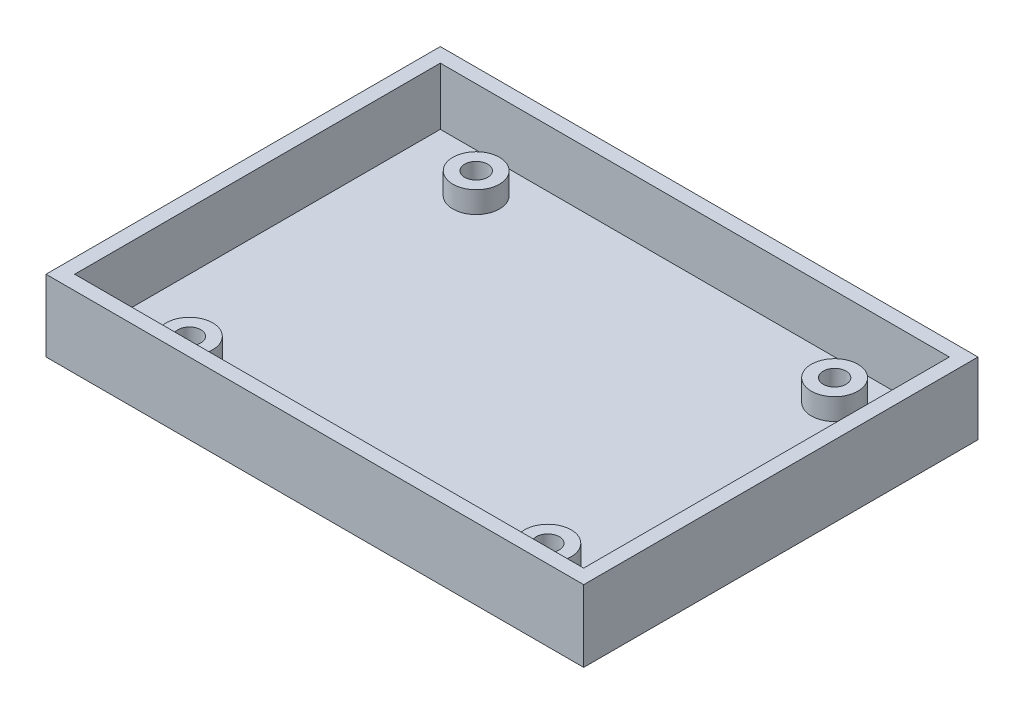
SolidWorks part; units mm, degrees
ref_plane "Front Plane" through (0, 0, 0) normal (0, 0, 1) x (1, 0, 0)
ref_plane "Top Plane" through (0, 0, 0) normal (0, 1, 0) x (1, 0, 0)
ref_plane "Right Plane" through (0, 0, 0) normal (1, 0, 0) x (0, 0, -1)
sketch "Sketch1" plane through (0, 0, 0) normal (0, 1, 0) x (1, 0, 0)
  line L1 (37.5, -27.5) -> (-37.5, -27.5)
  line L2 (37.5, -27.5) -> (37.5, 27.5)
  line L3 (37.5, 27.5) -> (-37.5, 27.5)
  line L4 (-37.5, -27.5) -> (-37.5, 27.5)
  line L5 (37.5, -27.5) -> (-37.5, 27.5) construction
  line L6 (37.5, 27.5) -> (-37.5, -27.5) construction
  point P0 (0, 0)
  dimension "D1" = 75
  dimension "D2" = 55
extrude "Body" add sketch "Sketch1" along normal blind 10
shell "Shell1" thickness 2
sketch "Sketch2" plane through (0, 2, 0) normal (0, 1, 0) x (1, 0, 0)
  line L1 (25, -20) -> (-25, -20) construction
  line L2 (25, -20) -> (25, 20) construction
  line L3 (25, 20) -> (-25, 20) construction
  line L4 (-25, -20) -> (-25, 20) construction
  line L5 (25, -20) -> (-25, 20) construction
  line L6 (25, 20) -> (-25, -20) construction
  circle A0 centre (-25, 20) radius 3.25
  circle A1 centre (25, 20) radius 3.25
  circle A2 centre (25, -20) radius 3.25
  circle A3 centre (-25, -20) radius 3.25
  point P0 (0, 0)
  dimension "D3" = 6.5
  dimension "D1" = 50
  dimension "D2" = 40
extrude "Inserts_Support" add sketch "Sketch2" along normal blind 3
sketch "Sketch3" plane through (0, 5, 0) normal (0, 1, 0) x (1, 0, 0)
  circle A0 centre (-25, 20) radius 1.6
  circle A1 centre (25, 20) radius 1.6
  circle A2 centre (25, -20) radius 1.6
  circle A3 centre (-25, -20) radius 1.6
  dimension "D1" = 3.2
extrude "Inserts_Holes" cut sketch "Sketch3" against normal blind 4
